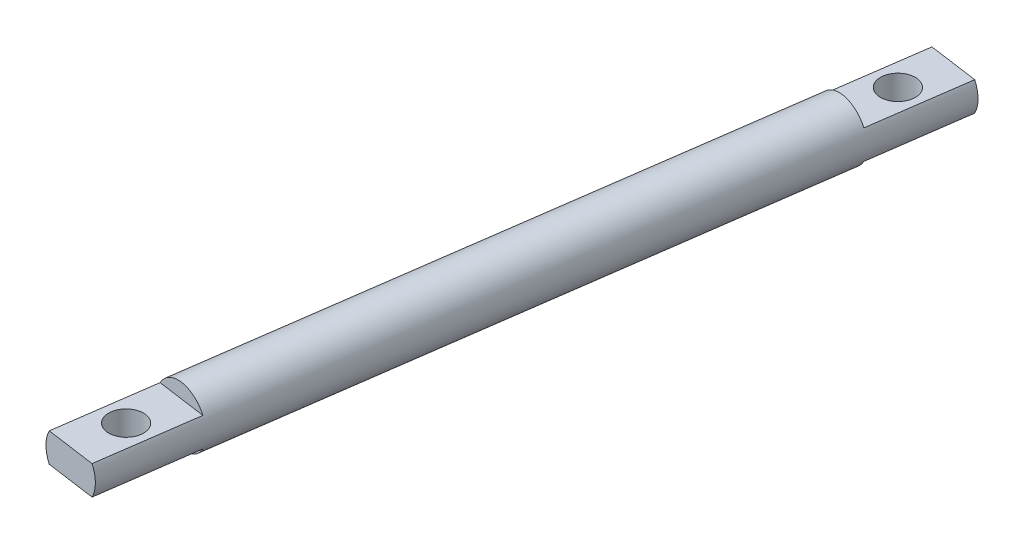
SolidWorks part; units mm, degrees
ref_plane "Front Plane" through (0, 0, 0) normal (0, 0, 1) x (1, 0, 0)
ref_plane "Top Plane" through (0, 0, 0) normal (0, 1, 0) x (1, 0, 0)
ref_plane "Right Plane" through (0, 0, 0) normal (1, 0, 0) x (0, 0, -1)
sketch "Sketch1" plane through (0, -11.1359, 0) normal (0, 1, 0) x (1, 0, 0)
  line L0 (-20.5731, 7.9375) -> (-23.7171, 8.3796) construction
  line L4 (-8.6719, 92.5676) -> (-11.816, 93.0098) construction
  line L5 (-14.1947, 76.0947) -> (-11.816, 93.0098) construction
  line L6 (-20.5731, 7.9375) -> (-23.7171, 8.3796)
  line L10 (-8.6719, 92.5676) -> (-11.816, 93.0098)
  line L11 (-14.1947, 76.0947) -> (-11.816, 93.0098)
  line L12 (-23.7171, 8.3796) -> (-21.3384, 25.2947) construction
  line L13 (-21.3384, 25.2947) -> (-14.1947, 76.0947) construction
  line L14 (-20.5731, 7.9375) -> (-8.6719, 92.5676) construction
  line L15 (-23.7171, 8.3796) -> (-21.3384, 25.2947)
  line L16 (-21.3384, 25.2947) -> (-14.1947, 76.0947)
  line L17 (-20.5731, 7.9375) -> (-8.6719, 92.5676)
revolve "Revolve1" add sketch "Sketch1" angle 360 about L11
ref_plane "Plane1" through (6.6462, 0, -47.2617) normal (-0.1393, 0, 0.9903) x (0.9903, 0, 0.1393)
sketch "Sketch2" plane through (-24.4127, 0, -3.433) normal (0.9903, 0, 0.1393) x (0.1393, 0, -0.9903)
  line L0 (4.9953, -12.7234) -> (15.7268, -12.7234) construction
  line L1 (4.9953, -9.5484) -> (15.7268, -9.5484) construction
  line L2 (15.7268, -7.9609) -> (4.9953, -7.9609) construction
  line L3 (4.9953, -14.3109) -> (4.9953, -7.9609) construction
  line L4 (15.7268, -14.3109) -> (4.9953, -14.3109) construction
  line L5 (15.7268, -14.3109) -> (15.7268, -7.9609) construction
  line L6 (4.9953, -12.7234) -> (15.7268, -12.7234)
  line L7 (4.9953, -9.5484) -> (15.7268, -9.5484)
  line L8 (15.7268, -7.9609) -> (4.9953, -7.9609)
  line L9 (4.9953, -14.3109) -> (4.9953, -7.9609)
  line L10 (15.7268, -14.3109) -> (4.9953, -14.3109)
  line L11 (15.7268, -14.3109) -> (15.7268, -7.9609)
extrude "Cut-Extrude1" cut sketch "Sketch2" against normal through all and the other way through all contours L10 L11 L6 L9 | L7 L11 L8 L9
sketch "Sketch3" plane through (0, -12.7234, 0) normal (0, -1, 0) x (1, 0, 0)
  circle A0 centre (-22.9699, -13.6931) radius 1.905 construction
  circle A1 centre (-22.9699, -13.6931) radius 1.905
extrude "Cut-Extrude2" cut sketch "Sketch3" against normal through all
ref_plane "Plane2" through (6.6462, 0, -47.2617) normal (-0.1393, 0, 0.9903) x (0.9903, 0, 0.1393)
mirror "Mirror1" about plane through (6.6462, 0, -47.2617) normal (-0.1393, 0, 0.9903) of "Cut-Extrude2", "Cut-Extrude1"
